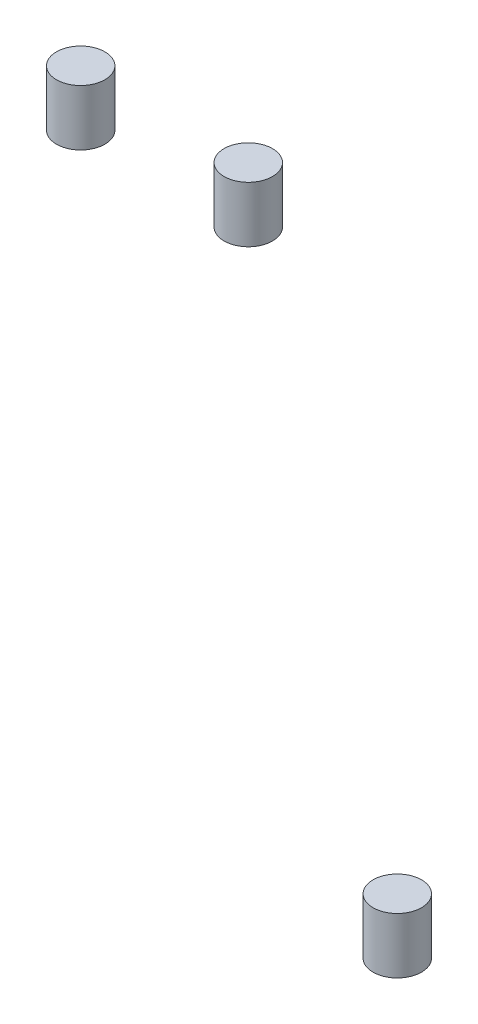
SolidWorks part; units mm, degrees
ref_plane "Front Plane" through (0, 0, 0) normal (0, 0, 1) x (1, 0, 0)
ref_plane "Top Plane" through (0, 0, 0) normal (0, 1, 0) x (1, 0, 0)
ref_plane "Right Plane" through (0, 0, 0) normal (1, 0, 0) x (0, 0, -1)
sketch "Sketch1" plane through (0, 0, 0) normal (0, 1, 0) x (1, 0, 0)
  circle A0 centre (450, -400) radius 130
extrude "Boss-Extrude1" add sketch "Sketch1" along normal blind 300 from offset 1750
sketch "Sketch2" plane through (0, 0, 0) normal (0, 1, 0) x (1, 0, 0)
  circle A0 centre (-450, -400) radius 130
extrude "Boss-Extrude2" add sketch "Sketch2" along normal blind 300 from offset 1750
sketch "Sketch3" plane through (0, 0, 0) normal (0, 1, 0) x (1, 0, 0)
  circle A0 centre (450, 400) radius 130
extrude "Boss-Extrude3" add sketch "Sketch3" along normal blind 300 from offset 2050
